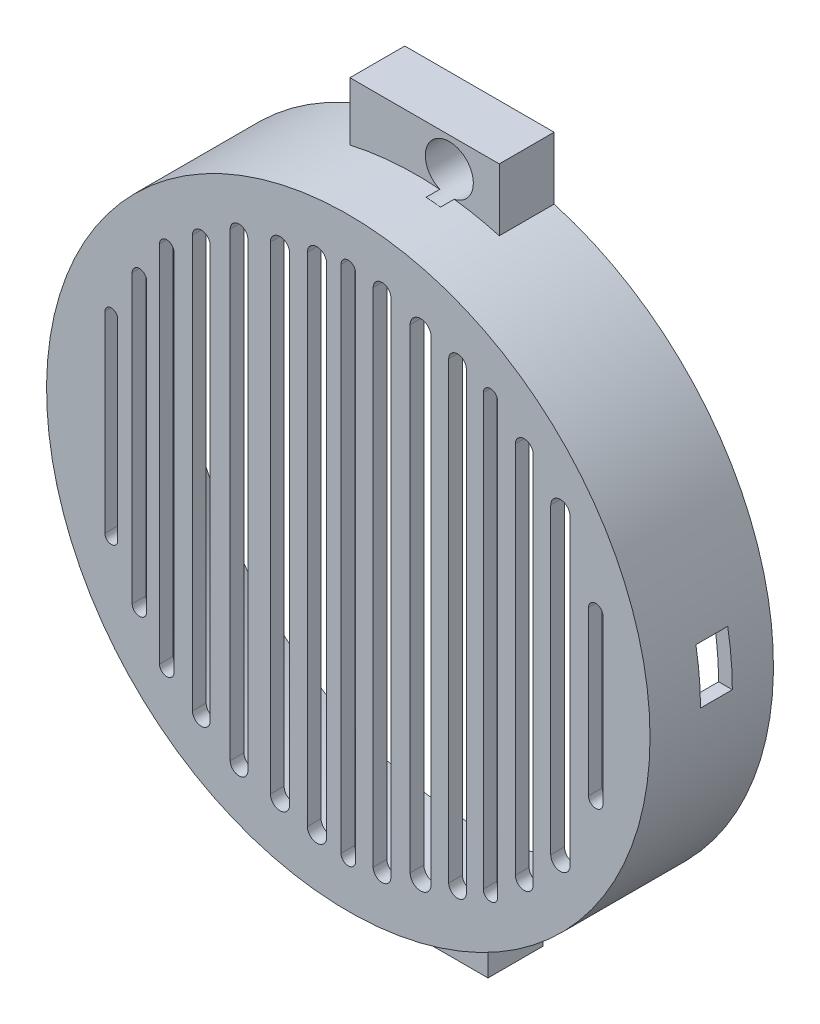
SolidWorks part; units mm, degrees
ref_plane "Front Plane" through (0, 0, 0) normal (0, 0, 1) x (1, 0, 0)
ref_plane "Top Plane" through (0, 0, 0) normal (0, 1, 0) x (1, 0, 0)
ref_plane "Right Plane" through (0, 0, 0) normal (1, 0, 0) x (0, 0, -1)
sketch "Sketch1" plane through (0, 0, 0) normal (0, 0, 1) x (1, 0, 0)
  circle A0 centre (0, 0) radius 22
  dimension "D1" = 44
extrude "Boss-Extrude1" add sketch "Sketch1" along normal blind 9
shell "Shell2" thickness 1
sketch "Sketch22" plane through (0, 0, 8) normal (0, 0, -1) x (-1, 0, 0)
  line L0 (0, -18.5966) -> (0, 18.5966) construction
  line L1 (-0.5271, -18.5966) -> (-0.5271, 18.5966)
  line L2 (0.5271, -18.5966) -> (0.5271, 18.5966)
  line L3 (2.2843, -18.128) -> (2.2843, 18.128) construction
  line L4 (1.5814, -18.128) -> (1.5814, 18.128)
  line L5 (2.9872, -18.128) -> (2.9872, 18.128)
  line L6 (4.9786, -17.4251) -> (4.9786, 17.4251) construction
  line L7 (4.2757, -17.4251) -> (4.2757, 17.4251)
  line L8 (5.6815, -17.4251) -> (5.6815, 17.4251)
  line L9 (7.9658, -16.7808) -> (7.9658, 16.7808) construction
  line L10 (7.3215, -16.7808) -> (7.3215, 16.7808)
  line L11 (8.6101, -16.7808) -> (8.6101, 16.7808)
  line L12 (10.7186, -15.0237) -> (10.7186, 15.0237) construction
  line L13 (10.0744, -15.0237) -> (10.0744, 15.0237)
  line L14 (11.3629, -15.0237) -> (11.3629, 15.0237)
  line L15 (13.2372, -13.2665) -> (13.2372, 13.2665) construction
  line L16 (12.7101, -13.2665) -> (12.7101, 13.2665)
  line L17 (13.7644, -13.2665) -> (13.7644, 13.2665)
  line L18 (15.2287, -10.4551) -> (15.2287, 10.4551) construction
  line L19 (14.7015, -10.4551) -> (14.7015, 10.4551)
  line L20 (15.7558, -10.4551) -> (15.7558, 10.4551)
  line L21 (17.2787, -6.9993) -> (17.2787, 6.9993) construction
  line L22 (16.8101, -6.9993) -> (16.8101, 6.9993)
  line L23 (17.7473, -6.9993) -> (17.7473, 6.9993)
  arc A0 (-0.5271, -18.5966) -> (0.5271, -18.5966) centre (0, -18.5966) ccw
  arc A1 (0.5271, 18.5966) -> (-0.5271, 18.5966) centre (0, 18.5966) ccw
  arc A2 (1.5814, -18.128) -> (2.9872, -18.128) centre (2.2843, -18.128) ccw
  arc A3 (2.9872, 18.128) -> (1.5814, 18.128) centre (2.2843, 18.128) ccw
  arc A4 (4.2757, -17.4251) -> (5.6815, -17.4251) centre (4.9786, -17.4251) ccw
  arc A5 (5.6815, 17.4251) -> (4.2757, 17.4251) centre (4.9786, 17.4251) ccw
  arc A6 (7.3215, -16.7808) -> (8.6101, -16.7808) centre (7.9658, -16.7808) ccw
  arc A7 (8.6101, 16.7808) -> (7.3215, 16.7808) centre (7.9658, 16.7808) ccw
  arc A8 (10.0744, -15.0237) -> (11.3629, -15.0237) centre (10.7186, -15.0237) ccw
  arc A9 (11.3629, 15.0237) -> (10.0744, 15.0237) centre (10.7186, 15.0237) ccw
  arc A10 (12.7101, -13.2665) -> (13.7644, -13.2665) centre (13.2372, -13.2665) ccw
  arc A11 (13.7644, 13.2665) -> (12.7101, 13.2665) centre (13.2372, 13.2665) ccw
  arc A12 (14.7015, -10.4551) -> (15.7558, -10.4551) centre (15.2287, -10.4551) ccw
  arc A13 (15.7558, 10.4551) -> (14.7015, 10.4551) centre (15.2287, 10.4551) ccw
  arc A14 (16.8101, -6.9993) -> (17.7473, -6.9993) centre (17.2787, -6.9993) ccw
  arc A15 (17.7473, 6.9993) -> (16.8101, 6.9993) centre (17.2787, 6.9993) ccw
  point P2 (0, 0)
  point P9 (2.2843, 0)
  point P16 (4.9786, 0)
  point P23 (7.9658, 0)
  point P30 (10.7186, 0)
  point P37 (13.2372, 0)
  point P44 (15.2287, 0)
  point P51 (17.2787, 0)
sketch "Sketch23" plane through (0, 0, 8) normal (0, 0, -1) x (-1, 0, 0)
  line L0 (-2.46, -18.3037) -> (-2.46, 18.3037) construction
  line L1 (-3.1043, -18.3037) -> (-3.1043, 18.3037)
  line L2 (-1.8157, -18.3037) -> (-1.8157, 18.3037)
  line L3 (-5.2715, -17.308) -> (-5.2715, 17.308) construction
  line L4 (-6.0329, -17.308) -> (-6.0329, 17.308)
  line L5 (-4.51, -17.308) -> (-4.51, 17.308)
  line L6 (-7.9658, -16.5465) -> (-7.9658, 16.5465) construction
  line L7 (-8.6101, -16.5465) -> (-8.6101, 16.5465)
  line L8 (-7.3215, -16.5465) -> (-7.3215, 16.5465)
  line L9 (-10.3672, -15.668) -> (-10.3672, 15.668) construction
  line L10 (-10.8944, -15.668) -> (-10.8944, 15.668)
  line L11 (-9.8401, -15.668) -> (-9.8401, 15.668)
  line L12 (-12.8272, -13.618) -> (-12.8272, 13.618) construction
  line L13 (-13.4715, -13.618) -> (-13.4715, 13.618)
  line L14 (-12.1829, -13.618) -> (-12.1829, 13.618)
  line L15 (-15.463, -11.0408) -> (-15.463, 11.0408) construction
  line L16 (-16.1658, -11.0408) -> (-16.1658, 11.0408)
  line L17 (-14.7601, -11.0408) -> (-14.7601, 11.0408)
  line L18 (-18.0401, -5.945) -> (-18.0401, 5.945) construction
  line L19 (-18.5673, -5.945) -> (-18.5673, 5.945)
  line L20 (-17.513, -5.945) -> (-17.513, 5.945)
  arc A0 (-3.1043, -18.3037) -> (-1.8157, -18.3037) centre (-2.46, -18.3037) ccw
  arc A1 (-1.8157, 18.3037) -> (-3.1043, 18.3037) centre (-2.46, 18.3037) ccw
  arc A2 (-6.0329, -17.308) -> (-4.51, -17.308) centre (-5.2715, -17.308) ccw
  arc A3 (-4.51, 17.308) -> (-6.0329, 17.308) centre (-5.2715, 17.308) ccw
  arc A4 (-8.6101, -16.5465) -> (-7.3215, -16.5465) centre (-7.9658, -16.5465) ccw
  arc A5 (-7.3215, 16.5465) -> (-8.6101, 16.5465) centre (-7.9658, 16.5465) ccw
  arc A6 (-10.8944, -15.668) -> (-9.8401, -15.668) centre (-10.3672, -15.668) ccw
  arc A7 (-9.8401, 15.668) -> (-10.8944, 15.668) centre (-10.3672, 15.668) ccw
  arc A8 (-13.4715, -13.618) -> (-12.1829, -13.618) centre (-12.8272, -13.618) ccw
  arc A9 (-12.1829, 13.618) -> (-13.4715, 13.618) centre (-12.8272, 13.618) ccw
  arc A10 (-16.1658, -11.0408) -> (-14.7601, -11.0408) centre (-15.463, -11.0408) ccw
  arc A11 (-14.7601, 11.0408) -> (-16.1658, 11.0408) centre (-15.463, 11.0408) ccw
  arc A12 (-18.5673, -5.945) -> (-17.513, -5.945) centre (-18.0401, -5.945) ccw
  arc A13 (-17.513, 5.945) -> (-18.5673, 5.945) centre (-18.0401, 5.945) ccw
  point P2 (-2.46, 0)
  point P8 (-5.2715, 0)
  point P15 (-7.9658, 0)
  point P22 (-10.3672, 0)
  point P29 (-12.8272, 0)
  point P36 (-15.463, 0)
  point P43 (-18.0401, 0)
extrude "Cut-Extrude1" cut sketch "Sketch23" against normal blind 5
extrude "Cut-Extrude2" cut sketch "Sketch22" against normal blind 5
ref_plane "Plane1" through (22, 0, 0) normal (1, 0, 0) x (0, 0, -1)
sketch "Sketch24" plane through (22, 0, 0) normal (1, 0, 0) x (0, 0, -1)
  line L0 (0, -22) -> (0, 22) construction
  line L1 (-5.3194, 0) -> (-3, 0)
  line L2 (-5.3194, 0) -> (-5.3194, 3.8335)
  line L3 (-5.3194, 3.8335) -> (-3, 3.8335)
  line L4 (-3, 0) -> (-3, 3.8335)
  dimension "D1" = 3
extrude "Cut-Extrude3" cut sketch "Sketch24" against normal blind 5
sketch "Sketch25" plane through (0, 0, 0) normal (0, 0, -1) x (-1, 0, 0)
  line L1 (-6.007, 21.164) -> (4.8806, 21.164)
  line L2 (-6.007, 21.164) -> (-6.007, 25.7043)
  line L3 (-6.007, 25.7043) -> (4.8806, 25.7043)
  line L4 (4.8806, 21.164) -> (4.8806, 25.7043)
  circle A0 centre (0, 0) radius 22 construction
extrude "Boss-Extrude2" add sketch "Sketch25" against normal blind 4 contours L2 L1 L4 L3
sketch "Sketch26" plane through (0, 0, 0) normal (0, 0, -1) x (-1, 0, 0)
  circle A0 centre (-2.3662, 23.5445) radius 1.75
  point P2 (-2.3662, 23.5445)
  dimension "D1" = 3.5
extrude "Cut-Extrude4" cut sketch "Sketch26" against normal blind 5
sketch "Sketch27" plane through (0, 0, 0) normal (0, 0, -1) x (-1, 0, 0)
  line L1 (-5.1866, -21.3799) -> (4.5717, -21.3799)
  line L2 (-5.1866, -21.3799) -> (-5.1866, -26.1103)
  line L3 (-5.1866, -26.1103) -> (4.5717, -26.1103)
  line L4 (4.5717, -21.3799) -> (4.5717, -26.1103)
  arc A0 (-6.007, 21.164) -> (4.8806, 21.4518) centre (0, 0) ccw construction
extrude "Boss-Extrude3" add sketch "Sketch27" against normal blind 4 contours L2 L1 L4 L3
sketch "Sketch28" plane through (0, 0, 0) normal (0, 0, -1) x (-1, 0, 0)
  circle A0 centre (0, -23.5982) radius 1.75
  dimension "D1" = 3.5
extrude "Cut-Extrude5" cut sketch "Sketch28" against normal blind 6
